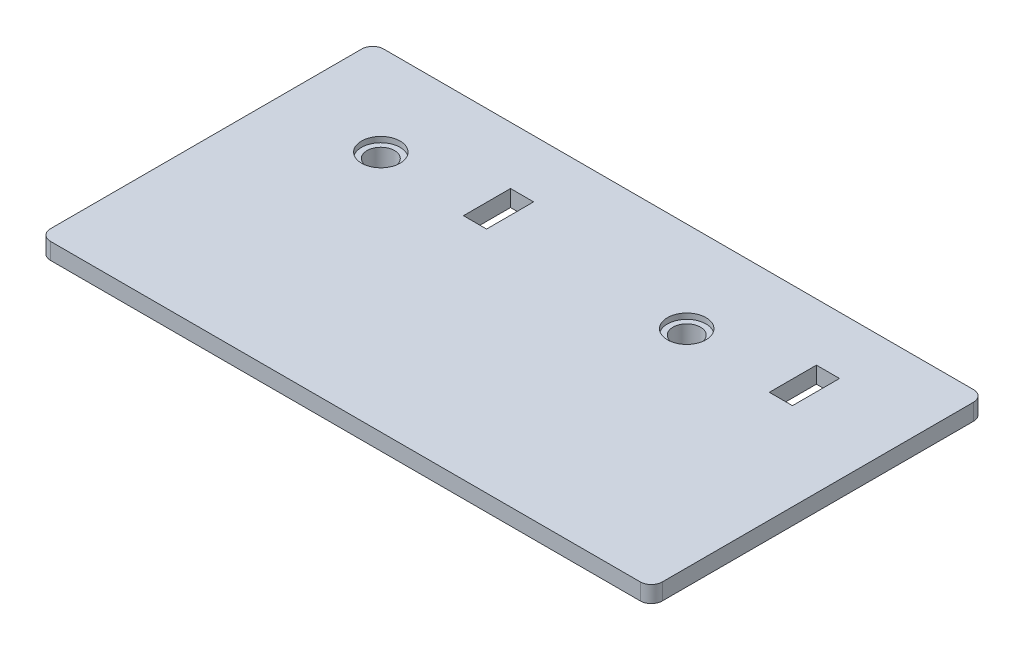
SolidWorks part; units mm, degrees
ref_plane "Front Plane" through (0, 0, 0) normal (0, 0, 1) x (1, 0, 0)
ref_plane "Top Plane" through (0, 0, 0) normal (0, 1, 0) x (1, 0, 0)
ref_plane "Right Plane" through (0, 0, 0) normal (1, 0, 0) x (0, 0, -1)
sketch "Sketch1" plane through (0, 0, 0) normal (0, 1, 0) x (1, 0, 0)
  line L1 (55.55, -30.25) -> (-55.55, -30.25)
  line L2 (55.55, -30.25) -> (55.55, 30.25)
  line L3 (55.55, 30.25) -> (-55.55, 30.25)
  line L4 (-55.55, -30.25) -> (-55.55, 30.25)
  line L5 (55.55, -30.25) -> (-55.55, 30.25) construction
  line L6 (55.55, 30.25) -> (-55.55, -30.25) construction
  point P0 (0, 0)
  dimension "D1" = 111.1
  dimension "D2" = 60.5
extrude "Boss-Extrude1" add sketch "Sketch1" along normal blind 3
sketch "Sketch9" plane through (0, 0, 0) normal (0, -1, 0) x (1, 0, 0)
  line L0 (-55.55, -30.25) -> (-55.55, 30.25) construction
  line L1 (-50.55, -23.25) -> (-45.55, -23.25)
  line L2 (-50.55, -23.25) -> (-50.55, -27.25)
  line L3 (-50.55, -27.25) -> (-45.55, -27.25)
  line L4 (-45.55, -23.25) -> (-45.55, -27.25)
  line L5 (-50.55, -23.25) -> (-45.55, -27.25) construction
  line L6 (-50.55, -27.25) -> (-45.55, -23.25) construction
  line L7 (55.55, -30.25) -> (-55.55, -30.25) construction
  line L8 (0, -30.25) -> (0, 30.25) construction
  line L9 (-55.55, 30.25) -> (55.55, 30.25) construction
  line L10 (50.55, -23.25) -> (50.55, -27.25)
  line L11 (50.55, -27.25) -> (45.55, -27.25)
  line L12 (45.55, -23.25) -> (45.55, -27.25)
  line L13 (50.55, -23.25) -> (45.55, -23.25)
  point P0 (-48.05, -25.25)
  dimension "D1" = 4
  dimension "D2" = 5
  dimension "D3" = 5
  dimension "D4" = 3
extrude "Boss-Extrude5" add sketch "Sketch9" along normal blind 3
fillet "Fillet1" radius 2 4 edges at (-55.55, 1.5, -30.25) (-55.55, 1.5, 30.25) (55.55, 1.5, 30.25) (55.55, 1.5, -30.25)
sketch "Sketch10" plane through (0, 3, 0) normal (0, 1, 0) x (1, 0, 0)
  line L0 (55.55, 11.28) -> (-44.5514, 11.28) construction
  line L1 (55.55, -28.25) -> (55.55, 28.25) construction
  line L2 (-53.55, -30.25) -> (53.55, -30.25) construction
  line L4 (39.65, 11.28) -> (35.45, 11.28)
  line L5 (39.65, 11.28) -> (39.65, 19.83)
  line L6 (39.65, 19.83) -> (35.45, 19.83)
  line L7 (35.45, 11.28) -> (35.45, 19.83)
  line L8 (-15.9, 11.28) -> (-20.1, 11.28)
  line L9 (-15.9, 11.28) -> (-15.9, 19.83)
  line L10 (-15.9, 19.83) -> (-20.1, 19.83)
  line L11 (-20.1, 11.28) -> (-20.1, 19.83)
  circle A0 centre (-37.6, 13.78) radius 2.5
  circle A1 centre (17.95, 13.78) radius 2.5
  dimension "D8" = 5
  dimension "D9" = 5
  dimension "D1" = 41.53
  dimension "D2" = 4.2
  dimension "D3" = 8.55
  dimension "D4" = 8.55
  dimension "D5" = 4.2
  dimension "D6" = 71.45
  dimension "D7" = 15.9
  dimension "D10" = 17.5
  dimension "D11" = 17.5
extrude "Cut-Extrude1" cut sketch "Sketch10" against normal blind 10
sketch "Sketch11" plane through (0, 3, 0) normal (0, 1, 0) x (1, 0, 0)
  circle A0 centre (-37.6, 13.78) radius 3.5
  circle A1 centre (17.95, 13.78) radius 3.5
  dimension "D1" = 7
  dimension "D2" = 7
extrude "Cut-Extrude2" cut sketch "Sketch11" against normal blind 1
sketch "Sketch12" plane through (0, 0, 0) normal (0, -1, 0) x (1, 0, 0)
  circle A0 centre (17.95, -13.78) radius 3.5
  circle A1 centre (-37.6, -13.78) radius 3.5
  circle A2 centre (17.95, -13.78) radius 2.5 construction
  circle A3 centre (-37.6, -13.78) radius 2.5 construction
  circle A4 centre (-37.6, -13.78) radius 2.5
  circle A5 centre (17.95, -13.78) radius 2.5
  dimension "D1" = 7
  dimension "D2" = 7
extrude "Boss-Extrude6" add sketch "Sketch12" along normal blind 5
